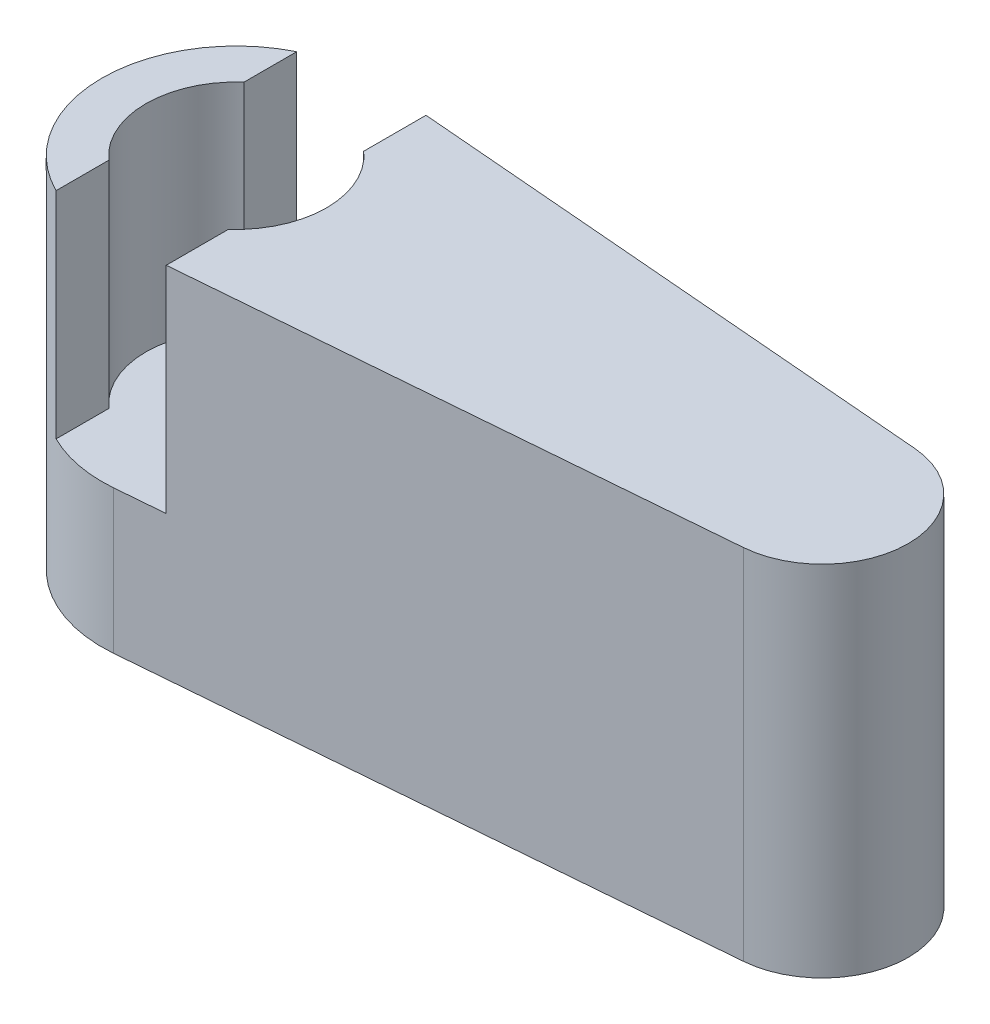
SolidWorks part; units mm, degrees
ref_plane "Front Plane" through (0, 0, 0) normal (0, 0, 1) x (1, 0, 0)
ref_plane "Top Plane" through (0, 0, 0) normal (0, 1, 0) x (1, 0, 0)
ref_plane "Right Plane" through (0, 0, 0) normal (1, 0, 0) x (0, 0, -1)
sketch "Sketch1" plane through (0, 0, 0) normal (0, 1, 0) x (1, 0, 0)
  line L0 (0.3096, -3.7372) -> (16.5482, -2.3918)
  line L1 (0.3096, 3.7372) -> (16.5482, 2.3918)
  line L2 (0, 0) -> (16.35, 0) construction
  arc A0 (0.3096, 3.7372) -> (0.3096, -3.7372) centre (0, 0) ccw
  arc A1 (16.5482, -2.3918) -> (16.5482, 2.3918) centre (16.35, 0) ccw
  arc A2 (3.75, 0) -> (0.3096, 3.7372) centre (0, 0) ccw construction
  arc A3 (0.3096, -3.7372) -> (3.75, 0) centre (0, 0) ccw construction
  point P7 (0, 0)
  dimension "D1" = 7.5
  dimension "D2" = 2.4
  dimension "D3" = 16.35
extrude "Boss-Extrude1" add sketch "Sketch1" along normal blind 10
sketch "Sketch2" plane through (0, 10, 0) normal (0, 1, 0) x (1, 0, 0)
  line L0 (-1.5, -1.809) -> (-1.5, -5.35) construction
  line L1 (-1.5, -5.35) -> (1.5, -5.35) construction
  line L2 (1.5, -5.35) -> (1.5, -1.809) construction
  line L3 (0, 0) -> (0, -2.35) construction
  line L4 (0, -2.35) -> (0, -5.35) construction
  line L5 (2.35, 0) -> (-2.35, 0) construction
  line L6 (-1.5, 1.809) -> (-1.5, 5.35) construction
  line L7 (-1.5, 5.35) -> (1.5, 5.35) construction
  line L8 (1.5, 5.35) -> (1.5, 1.809) construction
  line L9 (-1.67, -1.8872) -> (-1.67, -5.52)
  line L10 (-1.67, -5.52) -> (1.67, -5.52)
  line L11 (1.67, -5.52) -> (1.67, -1.8872)
  line L12 (1.67, 5.52) -> (1.67, 1.8872)
  line L13 (-1.67, 5.52) -> (1.67, 5.52)
  line L14 (-1.67, 1.8872) -> (-1.67, 5.52)
  arc A0 (1.5, -1.809) -> (1.5, 1.809) centre (0, 0) ccw construction
  arc A1 (-1.5, -1.809) -> (0, -2.35) centre (0, 0) ccw construction
  arc A2 (0, -2.35) -> (1.5, -1.809) centre (0, 0) ccw construction
  arc A3 (-1.5, 1.809) -> (-1.5, -1.809) centre (0, 0) ccw construction
  arc A4 (1.5, 1.809) -> (-1.5, 1.809) centre (0, 0) ccw construction
  arc A5 (1.67, -1.8872) -> (1.67, 1.8872) centre (0, 0) ccw
  arc A6 (-1.67, 1.8872) -> (-1.67, -1.8872) centre (0, 0) ccw
  point P12 (0, 0)
  dimension "D1" = 4.7
  dimension "D2" = 3
  dimension "D3" = 3
  dimension "D4" = 0.17
extrude "Cut-Extrude1" cut sketch "Sketch2" against normal blind 6
